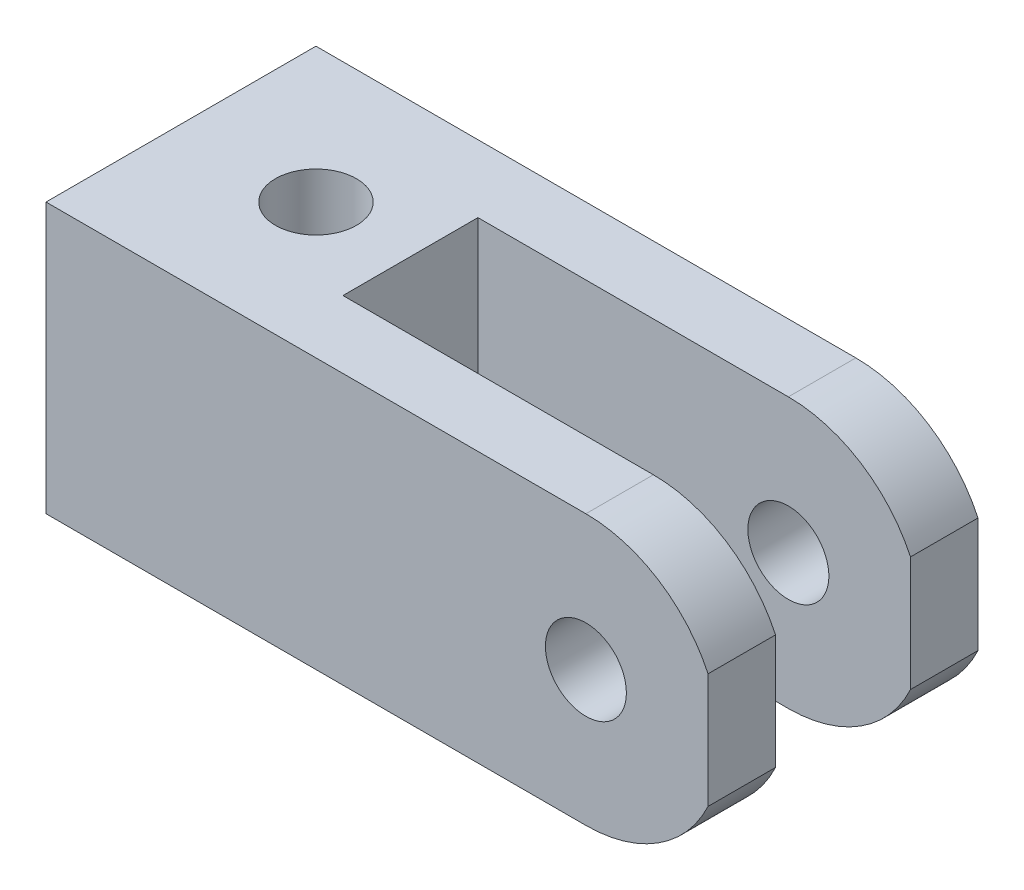
SolidWorks part; units mm, degrees
ref_plane "Alzado" through (0, 0, 0) normal (0, 0, 1) x (1, 0, 0)
ref_plane "Planta" through (0, 0, 0) normal (0, 1, 0) x (1, 0, 0)
ref_plane "Vista lateral" through (0, 0, 0) normal (1, 0, 0) x (0, 0, -1)
sketch "Croquis1" plane through (0, 0, 0) normal (0, 0, 1) x (1, 0, 0)
  line L1 (5, -5) -> (-20, -5)
  line L2 (5, -5) -> (5, 5)
  line L3 (5, 5) -> (-20, 5)
  line L4 (-20, -5) -> (-20, 5)
  circle A0 centre (0, 0) radius 1.5
  dimension "D2" = 3
  dimension "D1" = 25
  dimension "D3" = 10
  dimension "D4" = 5
  dimension "D5" = 5
extrude "Saliente-Extruir1" add sketch "Croquis1" along normal blind 10
sketch "Croquis2" plane through (0, 5, 0) normal (0, 1, 0) x (1, 0, 0)
  line L0 (-20, -10) -> (-20, 0) construction
  line L1 (5, 0) -> (-20, 0) construction
  circle A0 centre (-15, -5) radius 1.5
  dimension "D3" = 3
  dimension "D1" = 5
  dimension "D2" = 5
extrude "Cortar-Extruir1" cut sketch "Croquis2" against normal blind 14
sketch "Croquis3" plane through (5, 0, 0) normal (1, 0, 0) x (0, 0, -1)
  line L0 (-10, -5) -> (0, -5) construction
  line L1 (-7.5, -5) -> (-2.5, -5)
  line L2 (-7.5, -5) -> (-7.5, 5)
  line L3 (-7.5, 5) -> (-2.5, 5)
  line L4 (-2.5, -5) -> (-2.5, 5)
  line L5 (-10, -5) -> (-10, 5) construction
  line L6 (0, -5) -> (0, 5) construction
  dimension "D1" = 2.5
  dimension "D2" = 2.5
  dimension "D3" = 10
extrude "Cortar-Extruir2" cut sketch "Croquis3" against normal blind 16.5
sketch "Sketch1" plane through (0, 0, 10) normal (0, 0, 1) x (1, 0, 0)
  line L0 (0, 5) -> (0, -7.1106) construction
  line L1 (0, 5) -> (5.9929, 5)
  line L2 (5.9929, 5) -> (5.9929, -6.7488)
  line L3 (5.9929, -6.7488) -> (0, -5)
  line L4 (4.5251, 2.1269) -> (4.5251, -2.1269)
  arc A0 (0, -5) -> (4.5251, -2.1269) centre (0, 0) ccw
  arc A1 (4.5251, 2.1269) -> (0, 5) centre (0, 0) ccw
  dimension "D1" = 4.5251
extrude "Cut-Extrude1" cut sketch "Sketch1" against normal blind 10
sketch "Croquis5" plane through (0, -5, 0) normal (0, -1, 0) x (1, 0, 0)
  point P0 (-15, 5)
